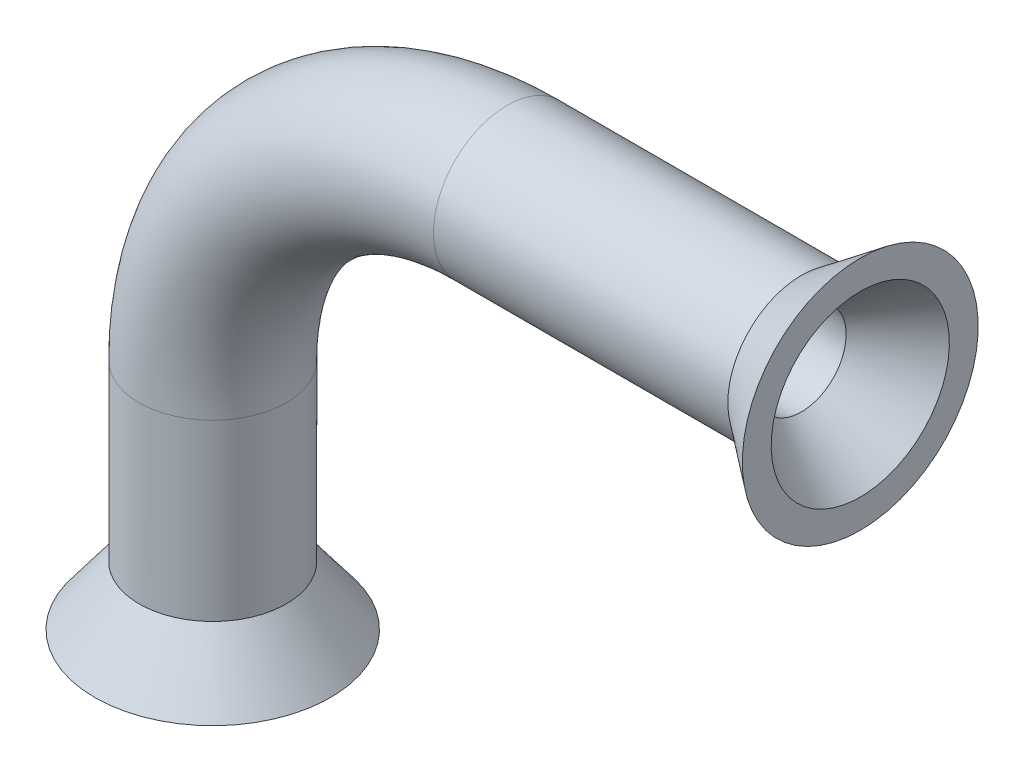
SolidWorks part; units mm, degrees
material "AISI 316 Annealed Stainless Steel Bar (SS)"
ref_plane "Front Plane" through (0, 0, 0) normal (0, 0, 1) x (1, 0, 0)
ref_plane "Top Plane" through (0, 0, 0) normal (0, 1, 0) x (1, 0, 0)
ref_plane "Right Plane" through (0, 0, 0) normal (1, 0, 0) x (0, 0, -1)
sketch "Sketch1" plane through (0, 0, 0) normal (0, 1, 0) x (1, 0, 0)
  circle A0 centre (0, 0) radius 3.175
  circle A1 centre (0, 0) radius 1.9304
  dimension "D1" = 6.35
  dimension "D2" = 1.2446
sketch "Sketch2" plane through (0, 0, 0) normal (0, 0, 1) x (1, 0, 0)
  line L0 (0, 0) -> (0, 7.5184)
  line L1 (12.7, 20.2184) -> (25.4, 20.2184)
  arc A0 (0, 7.5184) -> (12.7, 20.2184) centre (12.7, 7.5184) cw
  dimension "D1" = 20.2184
  dimension "D2" = 12.7
  dimension "D3" = 25.4
sweep "Sweep1" add profiles "Sketch1" path "Sketch2"
sketch "Sketch3" plane through (0, 0, 0) normal (0, -1, 0) x (1, 0, 0)
  circle A0 centre (0, 0) radius 3.175
  circle A1 centre (0, 0) radius 3.175 construction
extrude "Boss-Extrude1" add sketch "Sketch3" along normal blind 2.54 draft 37 draft outward yes
sketch "Sketch4" plane through (0, -2.54, 0) normal (0, -1, 0) x (1, 0, 0)
  line L0 (-3.175, 0) -> (-1.9304, 0) construction
  line L1 (-3.8444, 0) -> (-5.089, 0) construction
  circle A0 centre (0, 0) radius 3.8444
  circle A1 centre (0, 0) radius 3.175 construction
  circle A2 centre (0, 0) radius 1.9304 construction
  circle A3 centre (0, 0) radius 5.089 construction
extrude "Cut-Extrude1" cut sketch "Sketch4" against normal through all draft 37
sketch "Sketch5" plane through (25.4, 0, 0) normal (1, 0, 0) x (0, 0, -1)
  circle A1 centre (0, 20.2184) radius 3.175
  circle A2 centre (0, 20.2184) radius 3.175 construction
  circle A3 centre (0, 20.2184) radius 3.175 construction
extrude "Boss-Extrude2" add sketch "Sketch5" along normal blind 2.54 draft 37 draft outward yes
sketch "Sketch6" plane through (27.94, 0, 0) normal (1, 0, 0) x (0, 0, -1)
  line L0 (-3.8444, 20.2184) -> (-5.089, 20.2184) construction
  circle A0 centre (0, 20.2184) radius 3.8444
  circle A1 centre (0, 20.2184) radius 5.089 construction
  dimension "D1" = 1.2446
extrude "Cut-Extrude2" cut sketch "Sketch6" against normal through all draft 37
